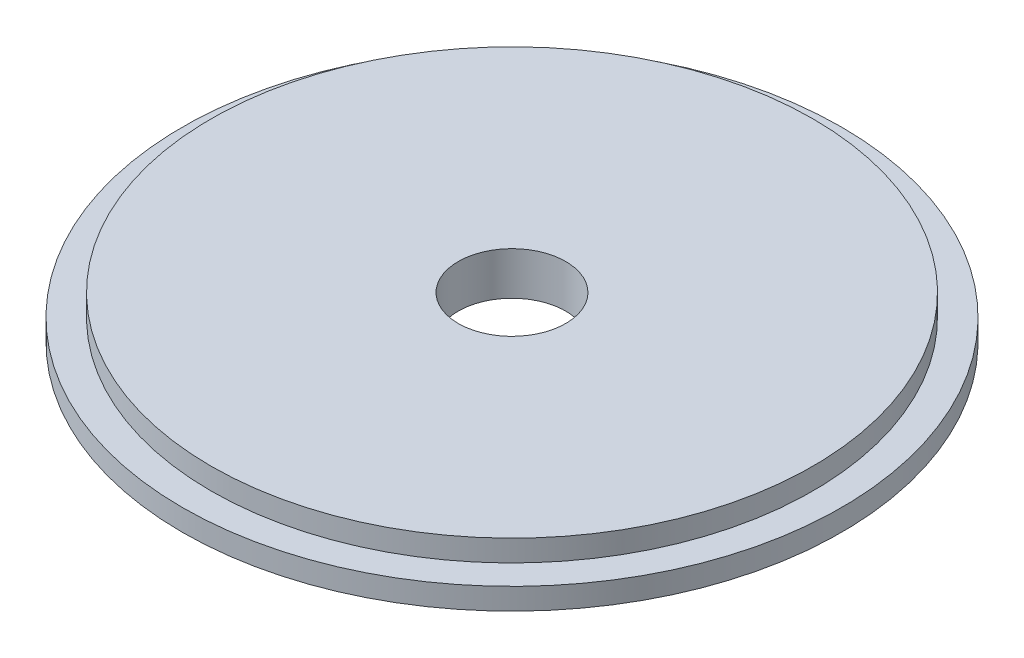
SolidWorks part; units mm, degrees
ref_plane "Front Plane" through (0, 0, 0) normal (0, 0, 1) x (1, 0, 0)
ref_plane "Top Plane" through (0, 0, 0) normal (0, 1, 0) x (1, 0, 0)
ref_plane "Right Plane" through (0, 0, 0) normal (1, 0, 0) x (0, 0, -1)
sketch "Sketch1" plane through (0, 0, 0) normal (0, 1, 0) x (1, 0, 0)
  circle A0 centre (0, 0) radius 23
  dimension "D1" = 46
extrude "Boss-Extrude1" add sketch "Sketch1" along normal blind 1.5
sketch "Sketch2" plane through (0, 1.5, 0) normal (0, 1, 0) x (1, 0, 0)
  circle A0 centre (0, 0) radius 21
  circle A2 centre (0, 0) radius 23 construction
  dimension "D1" = 2
extrude "Boss-Extrude2" add sketch "Sketch2" along normal blind 1.5
sketch "Sketch3" plane through (0, 3, 0) normal (0, 1, 0) x (1, 0, 0)
  circle A0 centre (0, 0) radius 3.75
  dimension "D1" = 7.5
extrude "Cut-Extrude2" cut sketch "Sketch3" against normal through all
